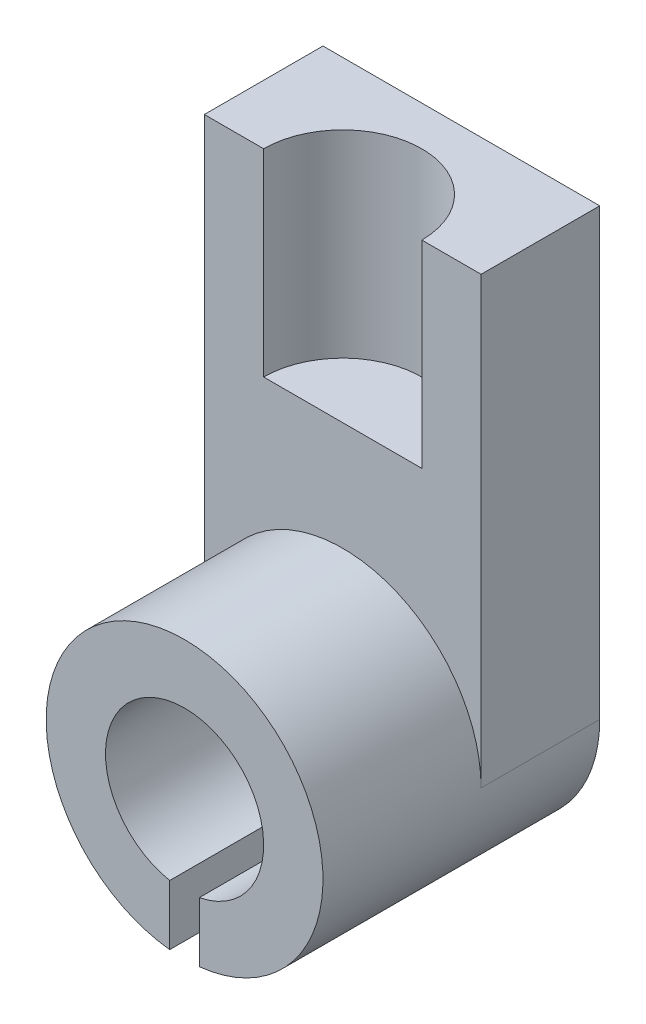
SolidWorks part; units mm, degrees
ref_plane "Front Plane" through (0, 0, 0) normal (0, 0, 1) x (1, 0, 0)
ref_plane "Top Plane" through (0, 0, 0) normal (0, 1, 0) x (1, 0, 0)
ref_plane "Right Plane" through (0, 0, 0) normal (1, 0, 0) x (0, 0, -1)
sketch "Sketch1" plane through (0, 0, 0) normal (0, 0, 1) x (1, 0, 0)
  line L2 (-3, -27.8388) -> (-3, -15.7162)
  line L4 (3, -15.7162) -> (3, -27.8388)
  arc A0 (3, -27.8388) -> (-3, -27.8388) centre (0, 0) ccw
  arc A1 (3, -15.7162) -> (-3, -15.7162) centre (0, 0) ccw
  dimension "D1" = 32
  dimension "D2" = 56
  dimension "D3" = 6
extrude "Boss-Extrude1" add sketch "Sketch1" along normal blind 56
ref_plane "Plane1" through (0, 90, 0) normal (0, 1, 0) x (1, 0, 0)
sketch "Sketch2" plane through (0, 90, 0) normal (0, 1, 0) x (1, 0, 0)
  line L5 (28, 0) -> (-28, 0) construction
  line L6 (-28, 0) -> (28, 0)
  line L7 (-28, 0) -> (-28, -24)
  line L8 (-28, -24) -> (28, -24)
  line L9 (28, 0) -> (28, -24)
  line L10 (-28, 0) -> (-28, -56) construction
  line L11 (28, -56) -> (28, 0) construction
  dimension "D1" = 24
extrude "Boss-Extrude2" add sketch "Sketch2" against normal up to next
sketch "Sketch3" plane through (0, 90, 0) normal (0, 1, 0) x (1, 0, 0)
  line L1 (-16, -24) -> (16, -24)
  circle A0 centre (0, -24) radius 16
  line M4 (-28, -24) -> (28, -24)
  dimension "D1" = 12
extrude "Cut-Extrude1" cut sketch "Sketch3" against normal blind 40 contours A0 M4
